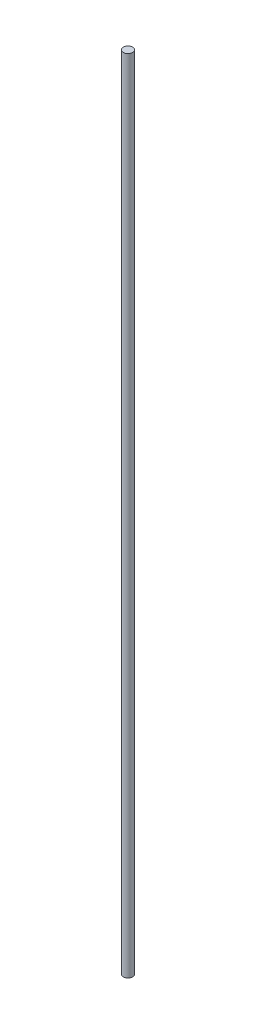
SolidWorks part; units mm, degrees
material "AISI 4340 Steel, normalized"
ref_plane "Front Plane" through (0, 0, 0) normal (0, 0, 1) x (1, 0, 0)
ref_plane "Top Plane" through (0, 0, 0) normal (0, 1, 0) x (1, 0, 0)
ref_plane "Right Plane" through (0, 0, 0) normal (1, 0, 0) x (0, 0, -1)
sketch "Sketch1" plane through (0, 0, 0) normal (0, 1, 0) x (1, 0, 0)
  circle A0 centre (0, 0) radius 2
  dimension "D1" = 4
extrude "Boss-Extrude1" add sketch "Sketch1" along normal blind 344
